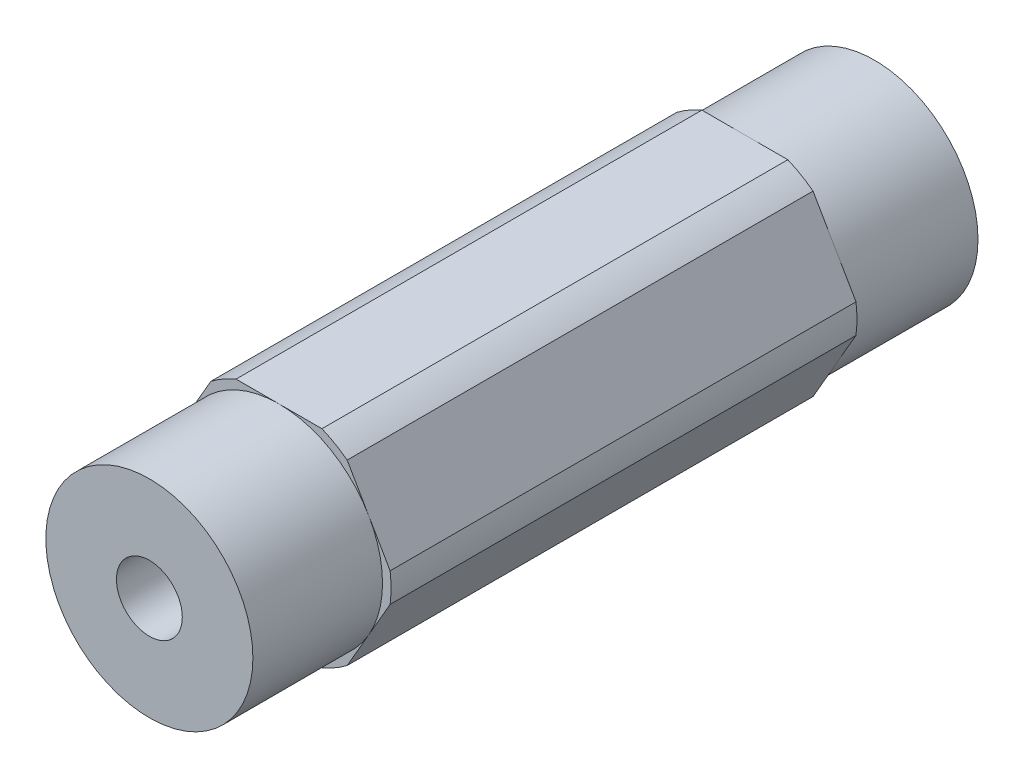
SolidWorks part; units mm, degrees
ref_plane "Front Plane" through (0, 0, 0) normal (0, 0, 1) x (1, 0, 0)
ref_plane "Top Plane" through (0, 0, 0) normal (0, 1, 0) x (1, 0, 0)
ref_plane "Right Plane" through (0, 0, 0) normal (1, 0, 0) x (0, 0, -1)
sketch "Sketch1" plane through (0, 0, 0) normal (0, 0, 1) x (1, 0, 0)
  line L1 (7.3323, 0) -> (3.6662, 6.35)
  line L2 (3.6662, 6.35) -> (-3.6662, 6.35)
  line L3 (-3.6662, 6.35) -> (-7.3323, 0)
  line L4 (-7.3323, 0) -> (-3.6662, -6.35)
  line L5 (-3.6662, -6.35) -> (3.6662, -6.35)
  line L6 (3.6662, -6.35) -> (7.3323, 0)
  circle A1 centre (0, 0) radius 6.35 construction
  circle A2 centre (0, 0) radius 2.0193
  dimension "D1" = 12.7
  dimension "D2" = 4.0386
extrude "Boss-Extrude1" add sketch "Sketch1" along normal mid plane 44.4754 contours L3 L4 L5 L6 L1 L2
sketch "Sketch2" plane through (0, 0, 22.2377) normal (0, 0, 1) x (1, 0, 0)
  circle A0 centre (0, 0) radius 6.35
extrude "Cut-Extrude2" cut sketch "Sketch2" against normal blind 7.9502 flip side to cut
mirror "Mirror1" about plane through (0, 0, 0) normal (0, 0, 1) of "Cut-Extrude2"
sketch "Sketch3" plane through (0, 0, 22.2377) normal (0, 0, 1) x (1, 0, 0)
  circle A0 centre (0, 0) radius 6.875
  dimension "D1" = 13.75
extrude "Cut-Extrude4" cut sketch "Sketch3" against normal through all flip side to cut
sketch "Sketch4" plane through (0, 0, 22.2377) normal (0, 0, 1) x (1, 0, 0)
  circle A0 centre (0, 0) radius 2.0193
  dimension "D1" = 4.0386
extrude "Cut-Extrude5" cut sketch "Sketch4" against normal through all
equation "\"D1@Boss-Extrude1\"=1.74600+0.005"
